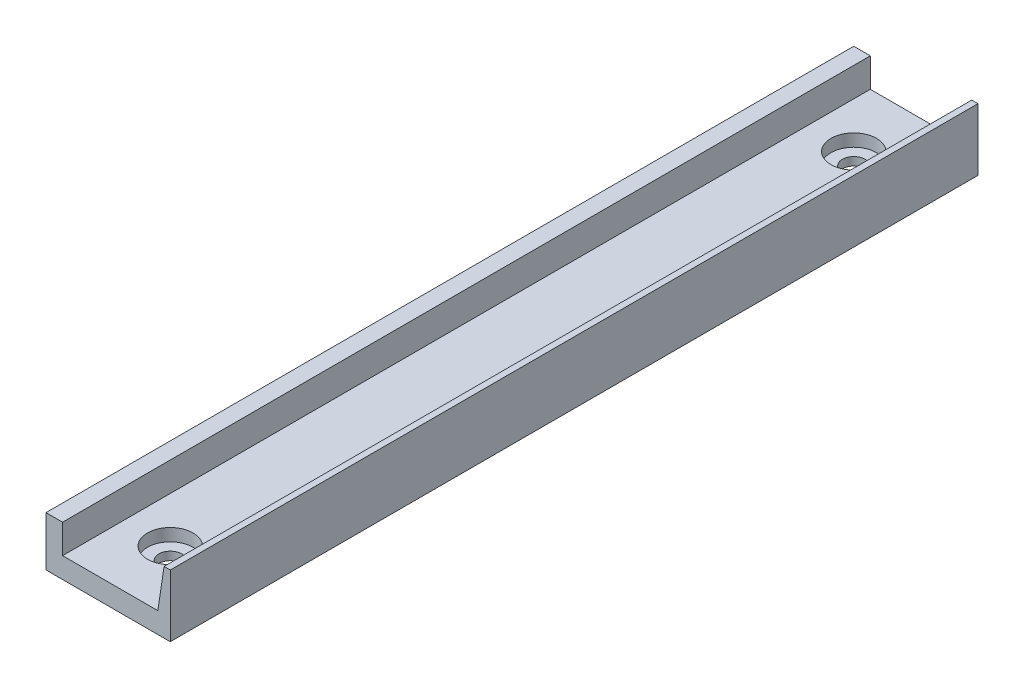
SolidWorks part; units mm, degrees
material "PLA"
ref_plane "정면" through (0, 0, 0) normal (0, 0, 1) x (1, 0, 0)
ref_plane "윗면" through (0, 0, 0) normal (0, 1, 0) x (1, 0, 0)
ref_plane "우측면" through (0, 0, 0) normal (1, 0, 0) x (0, 0, -1)
sketch "스케치1" plane through (0, 0, 0) normal (0, 1, 0) x (1, 0, 0)
  line L1 (-15, 97.5) -> (15, 97.5)
  line L2 (-15, 97.5) -> (-15, -97.5)
  line L3 (-15, -97.5) -> (15, -97.5)
  line L4 (15, 97.5) -> (15, -97.5)
  line L5 (-15, 97.5) -> (15, -97.5) construction
  line L6 (-15, -97.5) -> (15, 97.5) construction
  point P0 (0, 0)
  dimension "D1" = 195
  dimension "D2" = 30
extrude "보스-돌출1" add sketch "스케치1" along normal blind 5
sketch "스케치2" plane through (0, 5, 0) normal (0, 1, 0) x (1, 0, 0)
  line L0 (-15, -97.5) -> (15, -97.5) construction
  line L1 (-15, 97.5) -> (-11, 97.5)
  line L2 (-15, 97.5) -> (-15, -97.5)
  line L3 (-15, -97.5) -> (-11, -97.5)
  line L4 (-11, 97.5) -> (-11, -97.5)
  line L6 (15, 97.5) -> (12, 97.5)
  line L7 (15, 97.5) -> (15, -97.5)
  line L8 (15, -97.5) -> (12, -97.5)
  line L9 (12, 97.5) -> (12, -97.5)
  dimension "D1" = 4
  dimension "D2" = 3
extrude "보스-돌출2" add sketch "스케치2" along normal blind 10
sketch "스케치3" plane through (0, 0, 97.5) normal (0, 0, 1) x (1, 0, 0)
  line L11 (-11, 15) -> (-15, 15)
  line L13 (-15, 15) -> (-15, 12)
  line L14 (-15, 12) -> (-11, 12)
  line L15 (-11, 15) -> (-11, 5) construction
  line L16 (-11, 12) -> (-11, 15)
  line L19 (12, 5) -> (12, 15)
  line L20 (-15, 15) -> (-15, 0) construction
  line L24 (13.5, 15) -> (12, 5)
  line L25 (12, 15) -> (15, 15) construction
  line L26 (12, 15) -> (13.5, 15)
  dimension "D1" = 3
extrude "컷-돌출1" cut sketch "스케치3" against normal through all
hole_wizard "M5 소켓 머리 캡 나사용 카운터보어1" positions "스케치5" profile "스케치6" counterbore size "M5" standard "KS" end condition through all
sketch "스케치5" plane through (0, 5, 0) normal (0, 1, 0) x (1, 0, 0)
  line L0 (-11, -97.5) -> (12, -97.5) construction
  line L1 (12, 97.5) -> (-11, 97.5) construction
  line L3 (-15, 97.5) -> (-15, -97.5) construction
  point P0 (0, -82.5)
  point P2 (0, 82.5)
  dimension "D1" = 15
  dimension "D2" = 15
  dimension "D3" = 15
  dimension "D4" = 15
sketch "스케치6" plane through (0, 5, 82.5) normal (1, 0, 0) x (0, 0, 1)
  line L0 (0, 0) -> (0, 5)
  line L1 (0, 5) -> (2.75, 5)
  line L3 (2.75, 5) -> (2.75, 3)
  line L4 (2.75, 3) -> (5.5, 3)
  line L5 (5.5, 3) -> (5.5, 0)
  line L7 (5.5, 0) -> (0, 0)
  line L11 (0, -6.35) -> (0, 107.95) construction
  dimension "관통 구멍 지름" = 5.5
  dimension "관통 구멍 깊이" = 5
  dimension "카운터보어 지름" = 11
  dimension "카운터보어 깊이" = 3
sketch "스케치7" plane through (0, 0, 0) normal (0, -1, 0) x (1, 0, 0)
  line L1 (-3.05, 60) -> (3.05, 60)
  line L2 (-3.05, 60) -> (-3.05, -60)
  line L3 (-3.05, -60) -> (3.05, -60)
  line L4 (3.05, 60) -> (3.05, -60)
  line L5 (-3.05, 60) -> (3.05, -60) construction
  line L6 (-3.05, -60) -> (3.05, 60) construction
  point P0 (0, 0)
  dimension "D1" = 6.1
  dimension "D2" = 120
extrude "보스-돌출3" add sketch "스케치7" along normal blind 6
